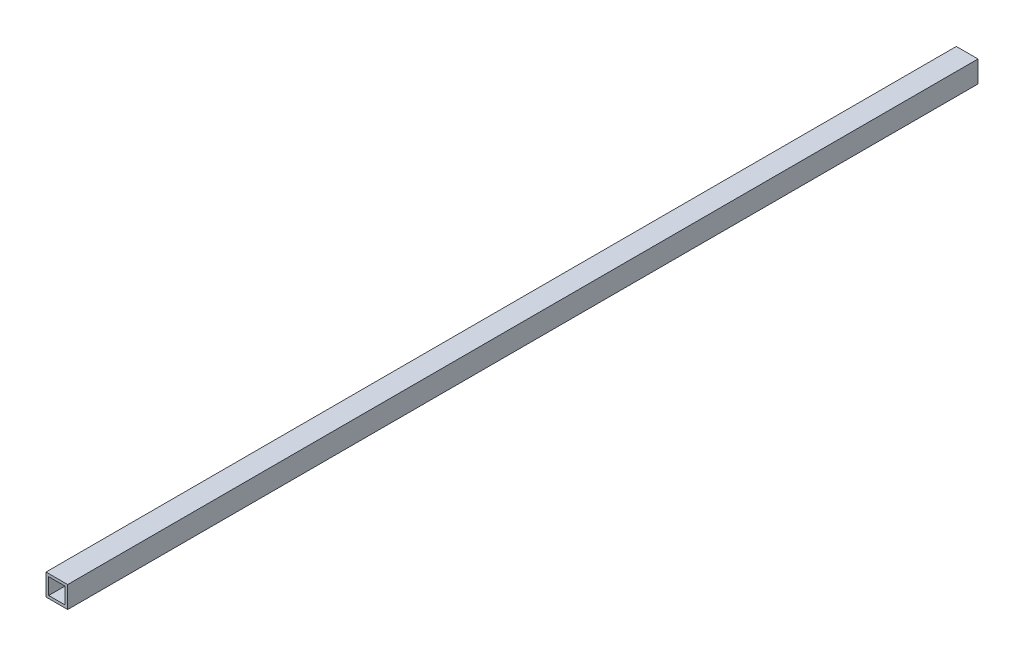
SolidWorks part; units mm, degrees
ref_plane "Front Plane" through (0, 0, 0) normal (0, 0, 1) x (1, 0, 0)
ref_plane "Top Plane" through (0, 0, 0) normal (0, 1, 0) x (1, 0, 0)
ref_plane "Right Plane" through (0, 0, 0) normal (1, 0, 0) x (0, 0, -1)
sketch "Sketch1" plane through (0, 0, 0) normal (0, 0, 1) x (1, 0, 0)
  line L0 (12.7, 0) -> (9.525, 0) construction
  line L1 (-12.7, 0) -> (12.7, 0) construction
  line L2 (0, 12.7) -> (0, -12.7)
  point P7 (0, 0)
sketch "Sketch2" plane through (0, 0, 0) normal (1, 0, 0) x (0, 0, -1)
  line L0 (533.4, 0) -> (-533.4, 0)
  point P4 (0, 0)
  dimension "Length" = 1066.8
sketch "Sketch3" plane through (0, 0, 0) normal (0, 0, 1) x (1, 0, 0)
  line L0 (-12.7, 0) -> (12.7, 0) construction
  line L5 (12.7, -12.7) -> (-12.7, -12.7)
  line L6 (12.7, -12.7) -> (12.7, 12.7)
  line L11 (12.7, 12.7) -> (-12.7, 12.7)
  line L12 (-12.7, -12.7) -> (-12.7, 12.7)
  line L14 (12.7, -12.7) -> (-12.7, 12.7) construction
  line L15 (12.7, 12.7) -> (-12.7, -12.7) construction
  line L16 (9.525, -9.525) -> (-9.525, -9.525)
  line L17 (9.525, -9.525) -> (9.525, 9.525)
  line L18 (9.525, 9.525) -> (-9.525, 9.525)
  line L19 (-9.525, -9.525) -> (-9.525, 9.525)
  line L20 (9.525, -9.525) -> (-9.525, 9.525) construction
  line L21 (9.525, 9.525) -> (-9.525, -9.525) construction
  point P0 (0, 0)
  point P5 (0, 0)
  point P13 (9.525, -12.7)
  dimension "D1" = 3.175
  dimension "D3" = 25.4
  dimension "D4" = 25.4
extrude "Boss-Extrude1" add sketch "Sketch3" along normal up to vertex (533.4 mm away) and the other way up to vertex (533.4 mm away) up to point (0, 0, 533.4) other way up to point (0, 0, -533.4)
sketch "Sketch5" plane through (0, 0, 0) normal (1, 0, 0) x (0, 0, -1)
  line L0 (-533.4, 0) -> (533.4, 0) construction
  line L3 (-533.4, -12.7) -> (-533.4, 12.7) construction
  line L4 (533.4, -12.7) -> (533.4, 12.7) construction
  point P6 (-504.825, 0)
  point P7 (-495.3, 0)
  point P8 (495.3, 0)
  point P10 (504.825, 0)
  dimension "D1" = 28.575
  dimension "D2" = 38.1
  dimension "D3" = 28.575
  dimension "D4" = 38.1
equation "\"D1@Sketch3\"=\"Wall thickness@Sketch1\""
equation "\"D1@Sketch5\"=\"Width@Sketch1\"*1.125"
equation "\"D2@Sketch5\"=\"Width@Sketch1\"*1.5"
equation "\"D3@Sketch5\"=\"D1@Sketch5\""
equation "\"D4@Sketch5\"=\"D2@Sketch5\""
equation "\"D2@Sketch3\"=\"Wall Thickness@Sketch1\""
